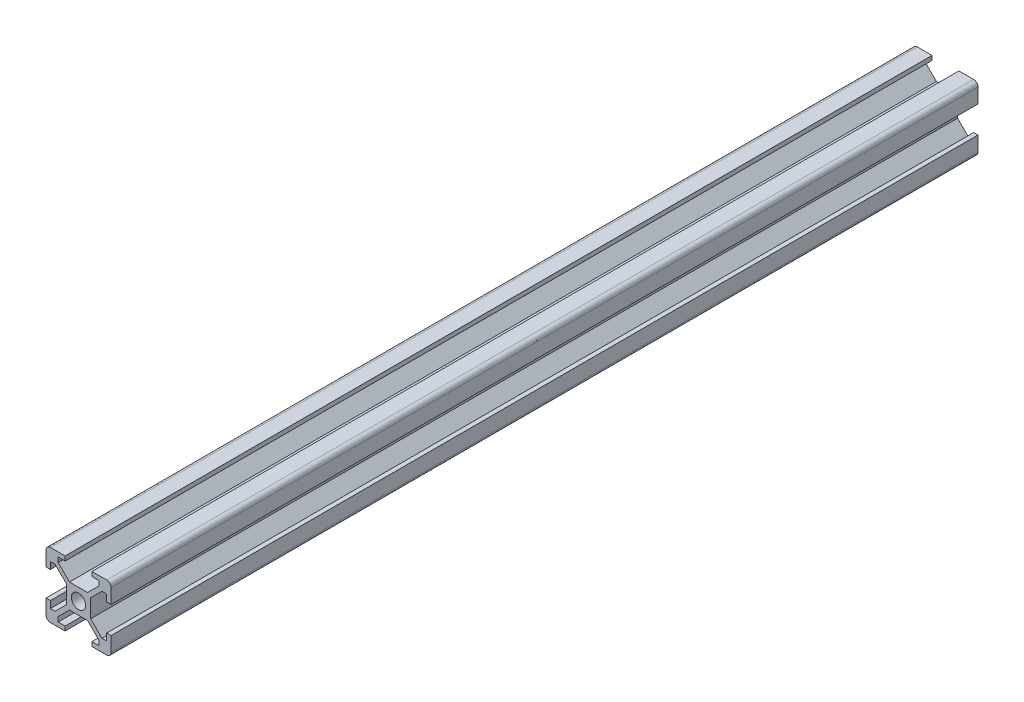
SolidWorks part; units mm, degrees
ref_plane "前视基准面" through (0, 0, 0) normal (0, 0, 1) x (1, 0, 0)
ref_plane "上视基准面" through (0, 0, 0) normal (0, 1, 0) x (1, 0, 0)
ref_plane "右视基准面" through (0, 0, 0) normal (1, 0, 0) x (0, 0, -1)
sketch "草图2" plane through (0, 0, 0) normal (0, 0, 1) x (1, 0, 0)
  line L1 (-2.0929, -2.8) -> (-4.7, -5.4071)
  line L2 (2.8, -2.0929) -> (2.8, 2.0929)
  line L3 (2.8, 2.0929) -> (5.4071, 4.7)
  line L4 (5.4071, 4.7) -> (6.5, 4.7)
  line L5 (6.5, 4.7) -> (6.5, 3.1)
  line L6 (6.5, 3.1) -> (7.5, 3.1)
  line L7 (7.5, 3.1) -> (7.5, 6.5)
  line L8 (-2.8, -2.0929) -> (-5.4071, -4.7)
  line L9 (-2.0929, 2.8) -> (2.0929, 2.8)
  line L10 (3.1, 7.5) -> (6.5, 7.5)
  line L11 (3.1, 6.5) -> (3.1, 7.5)
  line L12 (4.7, 6.5) -> (3.1, 6.5)
  line L13 (4.7, 5.4071) -> (4.7, 6.5)
  line L14 (2.0929, 2.8) -> (4.7, 5.4071)
  line L15 (-5.4071, 4.7) -> (-6.5, 4.7)
  line L16 (-6.5, 4.7) -> (-6.5, 3.1)
  line L17 (-6.5, 3.1) -> (-7.5, 3.1)
  line L18 (-7.5, 3.1) -> (-7.5, 6.5)
  line L19 (-4.7, 6.5) -> (-3.1, 6.5)
  line L20 (-3.1, 6.5) -> (-3.1, 7.5)
  line L21 (-3.1, 7.5) -> (-6.5, 7.5)
  line L22 (-4.7, 5.4071) -> (-4.7, 6.5)
  line L23 (-2.8, 2.0929) -> (-5.4071, 4.7)
  line L24 (-2.8, -2.0929) -> (-2.8, 2.0929)
  line L25 (-2.0929, 2.8) -> (-4.7, 5.4071)
  line L26 (-4.7, -5.4071) -> (-4.7, -6.5)
  line L27 (-3.1, -7.5) -> (-6.5, -7.5)
  line L28 (-3.1, -6.5) -> (-3.1, -7.5)
  line L29 (-4.7, -6.5) -> (-3.1, -6.5)
  line L30 (-7.5, -3.1) -> (-7.5, -6.5)
  line L31 (-6.5, -3.1) -> (-7.5, -3.1)
  line L32 (-6.5, -4.7) -> (-6.5, -3.1)
  line L33 (-5.4071, -4.7) -> (-6.5, -4.7)
  line L34 (2.0929, -2.8) -> (4.7, -5.4071)
  line L35 (4.7, -5.4071) -> (4.7, -6.5)
  line L36 (4.7, -6.5) -> (3.1, -6.5)
  line L37 (3.1, -6.5) -> (3.1, -7.5)
  line L38 (3.1, -7.5) -> (6.5, -7.5)
  line L39 (-2.0929, -2.8) -> (2.0929, -2.8)
  line L40 (7.5, -3.1) -> (7.5, -6.5)
  line L41 (6.5, -3.1) -> (7.5, -3.1)
  line L42 (6.5, -4.7) -> (6.5, -3.1)
  line L43 (5.4071, -4.7) -> (6.5, -4.7)
  line L44 (2.8, -2.0929) -> (5.4071, -4.7)
  arc A0 (7.5, 6.5) -> (6.5, 7.5) centre (6.5, 6.5) ccw
  arc A1 (-7.5, 6.5) -> (-6.5, 7.5) centre (-6.5, 6.5) cw
  arc A2 (-7.5, -6.5) -> (-6.5, -7.5) centre (-6.5, -6.5) ccw
  arc A3 (7.5, -6.5) -> (6.5, -7.5) centre (6.5, -6.5) cw
  circle A4 centre (0, 0) radius 1.65
  point P3 (0, -2.8)
  point P21 (7.5, 7.5)
  point P36 (0, 2.8)
  point P43 (-2.8, 0)
  point P60 (2.8, 0)
  point P61 (7.5, -7.5)
  dimension "D9" = 1
  dimension "D1" = 3.3
  dimension "D5" = 1
  dimension "D8" = 1
extrude "凸台-拉伸1" add sketch "草图2" along normal mid plane 200
